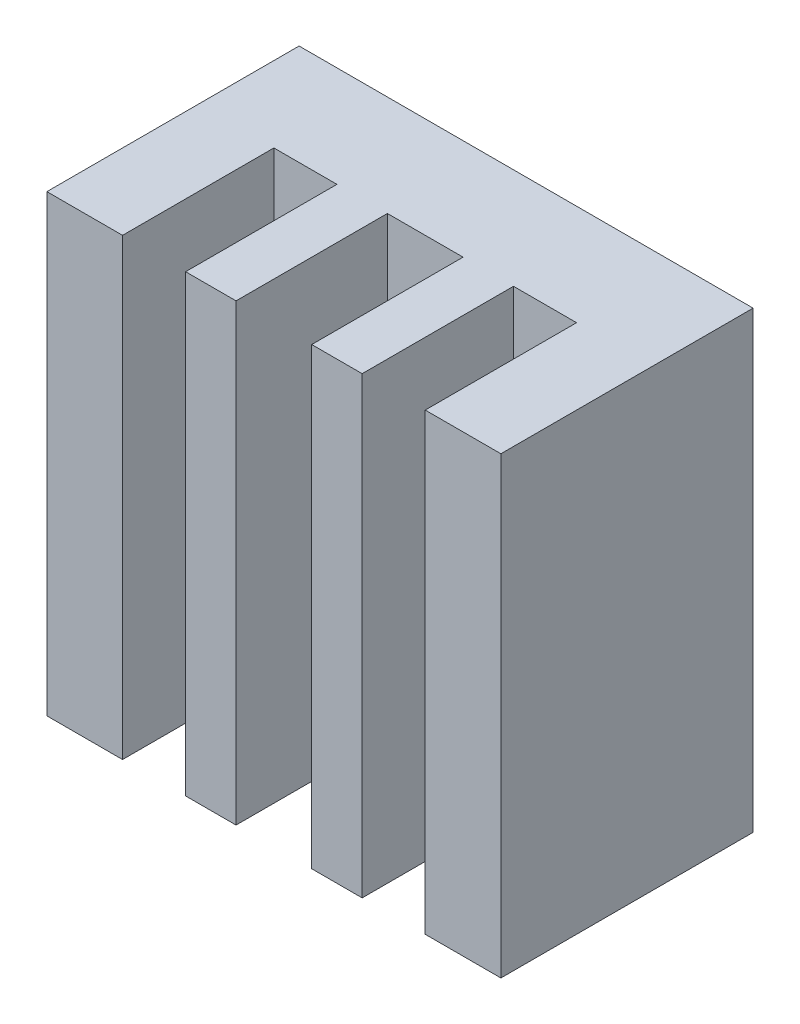
SolidWorks part; units mm, degrees
material "1060 合金"
ref_plane "前视基准面" through (0, 0, 0) normal (0, 0, 1) x (1, 0, 0)
ref_plane "上视基准面" through (0, 0, 0) normal (0, 1, 0) x (1, 0, 0)
ref_plane "右视基准面" through (0, 0, 0) normal (1, 0, 0) x (0, 0, -1)
other "Configuration Table"
sketch "草图1" plane through (0, 0, 0) normal (0, 0, 1) x (1, 0, 0)
  line L1 (0, 0) -> (9, 0)
  line L2 (0, 0) -> (0, 9)
  line L3 (0, 9) -> (9, 9)
  line L4 (9, 0) -> (9, 9)
  dimension "D1" = 9
  dimension "D2" = 9
extrude "凸台-拉伸1" add sketch "草图1" along normal blind 5
sketch "草图2" plane through (0, 0, 0) normal (0, -1, 0) x (1, 0, 0)
  line L0 (9, 5) -> (9, 0) construction
  line L1 (0, 5) -> (9, 5)
  line L2 (0, 5) -> (0, 2)
  line L3 (0, 2) -> (9, 2)
  line L4 (9, 5) -> (9, 2)
  line L6 (1.5, 5) -> (2.75, 5)
  line L7 (1.5, 5) -> (1.5, 2)
  line L8 (1.5, 2) -> (2.75, 2)
  line L9 (2.75, 5) -> (2.75, 2)
  line L10 (3.75, 5) -> (4.5, 5)
  line L11 (3.75, 5) -> (3.75, 2)
  line L12 (3.75, 2) -> (4.5, 2)
  line L13 (4.5, 5) -> (4.5, 2)
  line L14 (4.5, 5) -> (5.25, 5)
  line L15 (4.5, 5) -> (4.5, 2)
  line L16 (4.5, 2) -> (5.25, 2)
  line L17 (5.25, 5) -> (5.25, 2)
  line L18 (6.25, 5) -> (7.5, 5)
  line L19 (6.25, 5) -> (6.25, 2)
  line L20 (6.25, 2) -> (7.5, 2)
  line L21 (7.5, 5) -> (7.5, 2)
  dimension "D1" = 3
  dimension "D2" = 1.5
  dimension "D3" = 1
  dimension "D4" = 0.75
  dimension "D5" = 0.75
  dimension "D6" = 1
  dimension "D7" = 1.5
extrude "切除-拉伸1" cut sketch "草图2" against normal blind 10 contours L9 L1 L7 L3 | L13 L1 L11 L3 | L17 L1 L13 L3 | L21 L1 L19 L3
